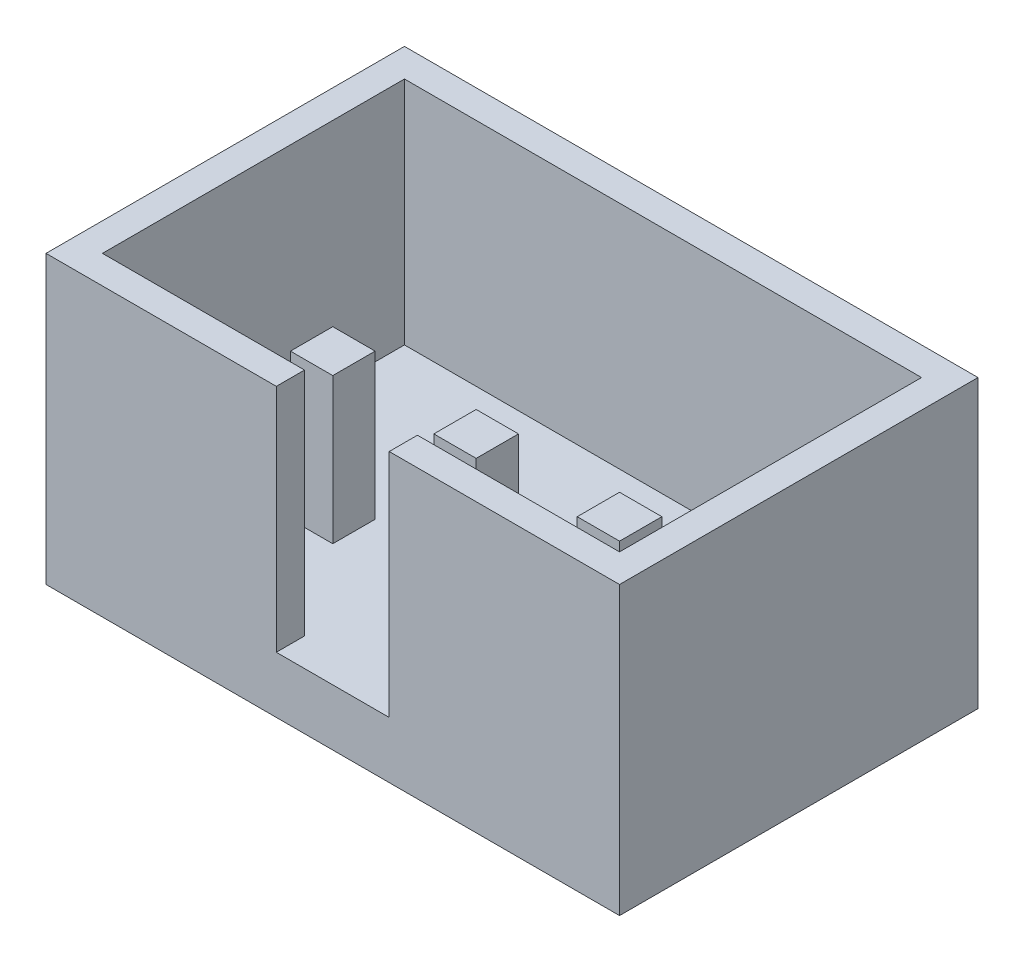
SolidWorks part; units mm, degrees
ref_plane "前视基准面" through (0, 0, 0) normal (0, 0, 1) x (1, 0, 0)
ref_plane "上视基准面" through (0, 0, 0) normal (0, 1, 0) x (1, 0, 0)
ref_plane "右视基准面" through (0, 0, 0) normal (1, 0, 0) x (0, 0, -1)
sketch "草图1" plane through (0, 0, 0) normal (0, 1, 0) x (1, 0, 0)
  line L0 (0, 7.1914) -> (0, -5.4429) construction
  line L1 (-5.08, 3.175) -> (5.08, 3.175)
  line L2 (-5.08, 3.175) -> (-5.08, -3.175)
  line L3 (-5.08, -3.175) -> (5.08, -3.175)
  line L4 (5.08, 3.175) -> (5.08, -3.175)
  line L5 (-10.6234, 0) -> (16.1963, 0) construction
  dimension "D1" = 10.16
  dimension "D2" = 6.35
extrude "拉伸1" add sketch "草图1" along normal blind 5.08
sketch "草图2" plane through (0, 5.08, 0) normal (0, 1, 0) x (-1, 0, 0)
  line L8 (4.58, -2.675) -> (4.58, 2.675)
  line L9 (4.58, 2.675) -> (-4.58, 2.675)
  line L10 (-4.58, 2.675) -> (-4.58, -2.675)
  line L11 (-4.58, -2.675) -> (4.58, -2.675)
  line L12 (4.58, -2.675) -> (4.58, 2.675)
  line L13 (4.58, 2.675) -> (-4.58, 2.675)
  line L14 (-4.58, 2.675) -> (-4.58, -2.675)
  line L15 (-4.58, -2.675) -> (4.58, -2.675)
  dimension "D1" = 0.5
extrude "切除-拉伸1" cut sketch "草图2" against normal offset from surface (4.08 mm away) 1 up to face at (0, 0, 0)
sketch "草图3" plane through (0, 0, 3.175) normal (0, 0, 1) x (1, 0, 0)
  line L0 (-5.08, 5.08) -> (5.08, 5.08) construction
  line L1 (-1, 5.08) -> (1, 5.08)
  line L2 (-1, 5.08) -> (-1, 1)
  line L3 (-1, 1) -> (1, 1)
  line L4 (1, 5.08) -> (1, 1)
  line L5 (4.58, 1) -> (-4.58, 1) construction
  line L6 (0, -1.5083) -> (0, 12.2426) construction
  dimension "D1" = 2
extrude "切除-拉伸2" cut sketch "草图3" against normal blind 1
sketch "草图4" plane through (0, 0, 0) normal (0, -1, 0) x (1, 0, 0)
  line L0 (7.6775, 0.635) -> (-8.5467, 0.635) construction
  line L2 (0, -3.6953) -> (0, 4.0669) construction
  line L3 (0, 2.1009) -> (0, -0.7012) construction
  line L4 (-0.375, 1.01) -> (0.375, 1.01)
  line L5 (-0.375, 1.01) -> (-0.375, 0.26)
  line L6 (-0.375, 0.26) -> (0.375, 0.26)
  line L7 (0.375, 1.01) -> (0.375, 0.26)
  line L8 (2.165, 1.01) -> (2.915, 1.01)
  line L9 (2.165, 1.01) -> (2.165, 0.26)
  line L10 (2.165, 0.26) -> (2.915, 0.26)
  line L11 (2.915, 1.01) -> (2.915, 0.26)
  line L16 (-2.915, 1.01) -> (-2.165, 1.01)
  line L17 (-2.915, 1.01) -> (-2.915, 0.26)
  line L18 (-2.915, 0.26) -> (-2.165, 0.26)
  line L19 (-2.165, 1.01) -> (-2.165, 0.26)
  line L20 (4.705, 1.01) -> (5.455, 1.01) [skipped]
  line L21 (4.705, 1.01) -> (4.705, 0.26) [skipped]
  line L22 (4.705, 0.26) -> (5.455, 0.26) [skipped]
  line L23 (5.455, 1.01) -> (5.455, 0.26) [skipped]
  dimension "D2" = 0.75
  dimension "D3" = 0.75
  dimension "D4" = 0
extrude "拉伸2" add sketch "草图4" along normal blind 2 and the other way offset from surface (3.58 mm away) 1.5 other way up to face at (0, 5.08, 0.975)
